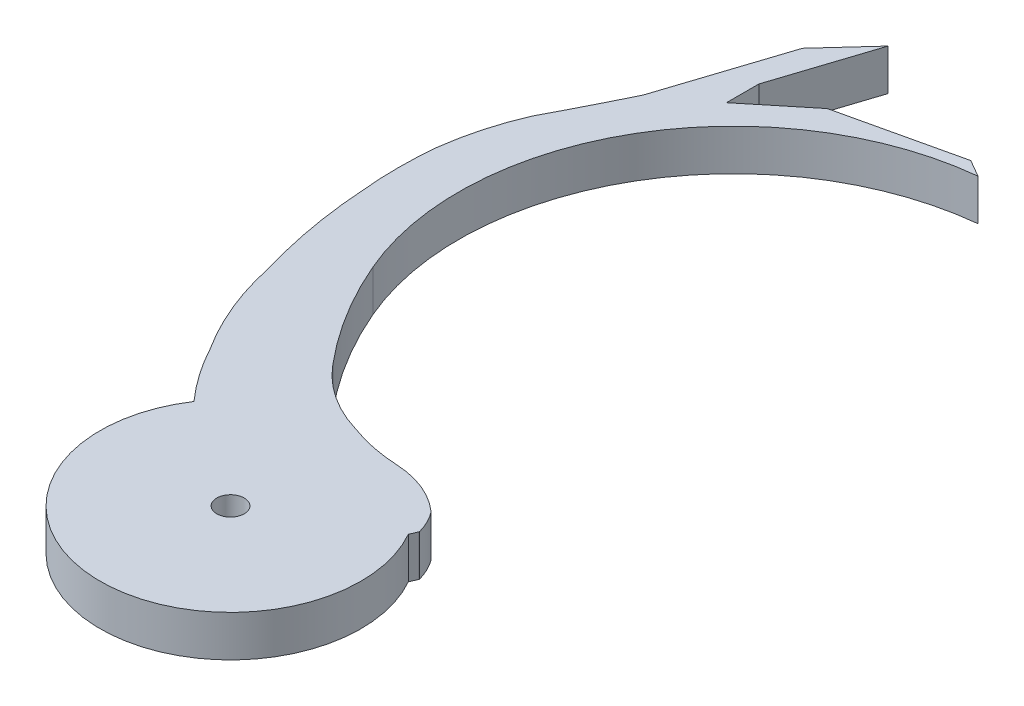
SolidWorks part; units mm, degrees
ref_plane "Front Plane" through (0, 0, 0) normal (0, 0, 1) x (1, 0, 0)
ref_plane "Top Plane" through (0, 0, 0) normal (0, 1, 0) x (1, 0, 0)
ref_plane "Right Plane" through (0, 0, 0) normal (1, 0, 0) x (0, 0, -1)
sketch "Sketch2" plane through (0, 0, 0) normal (0, 1, 0) x (1, 0, 0)
  line L0 (0, 0) -> (-35.9464, 0) construction
  line L1 (-35.9464, 0) -> (41.3976, 0) construction
  line L2 (41.3976, 0) -> (0, 0) construction
  line L3 (0, 0) -> (0, 18.7982) construction
  line L4 (0, 18.7982) -> (0, -23.465) construction
  circle A0 centre (0, 0) radius 20 construction
  circle A1 centre (0, 0) radius 23.465
sketch "Sketch4" plane through (0, 0, 0) normal (0, 1, 0) x (1, 0, 0)
  line L0 (-19.7005, -1.3216) -> (20.2972, -0.8891) construction
  circle A0 centre (0, 0) radius 23.4639 construction
  dimension "D1" = 40
sketch "Sketch5" plane through (0, 0, 0) normal (0, 1, 0) x (1, 0, 0)
  line L0 (-19.9303, -0.0851) -> (20.0695, 0.0365) construction
  dimension "D1" = 40
sketch "Sketch6" plane through (0, 0, 0) normal (0, 1, 0) x (1, 0, 0)
  circle A0 centre (-4.3374, 0.8589) radius 20
sketch "sungu kiri " plane through (0, 0, 0) normal (0, 1, 0) x (1, 0, 0)
  line L0 (-17.9037, 25.6768) -> (-20.2142, 18.582)
  line L1 (-20.2142, 18.582) -> (-20.2142, 16.2232)
  line L2 (-16.1729, 19.5215) -> (-7.6679, 21.4704)
  line L4 (-17.9037, 25.6768) -> (-20.8793, 22.4196)
  line L5 (-20.8793, 22.4196) -> (-23.726, 13.6785)
  line L6 (-23.3814, 7.2187) -> (-21.0655, 13.8643)
  line L8 (-21.0655, 13.8643) -> (-20.2142, 18.582)
  line L9 (-7.6679, 21.4704) -> (-6.4236, 20.7498)
  line L10 (-4.3374, 0.8589) -> (-4.3374, 13.8643) construction
  line L14 (-16.1729, 19.5215) -> (-20.2142, 16.2232)
  line L24 (-4.3374, 0.8589) -> (-4.3374, -17.8442) construction
  arc A0 (-4.3374, -21.9985) -> (-5.1555, -20.3392) centre (-9.0425, -23.287) ccw
  arc A1 (-5.1555, -20.3392) -> (-9.3619, -18.6184) centre (-9.6898, -25.4217) ccw
  arc A2 (-9.3619, -18.6184) -> (-13.1502, -17.8442) centre (-8.7528, -5.9825) cw
  arc A3 (-13.1502, -17.8442) -> (-18.7296, -13.6646) centre (-10.3234, -8.257) cw
  arc A4 (-22.7226, -7.0141) -> (-17.1413, 16.2232) centre (-4.3374, 0.8589) cw
  arc A8 (-23.726, 13.6785) -> (-26.4444, 8.3095) centre (-176.3922, 87.6034) cw
  arc A9 (-26.4444, 8.3095) -> (-27.9369, 2.8451) centre (-7.9567, 0.3238) ccw
  arc A10 (-27.9369, 2.8451) -> (-27.9369, -2.4841) centre (-0.9166, 0.1805) ccw
  arc A11 (-27.9369, -2.4841) -> (-26.4444, -10.8627) centre (10.027, -0.0436) ccw
  arc A12 (-26.4444, -10.8627) -> (-23.4884, -18.0953) centre (-5.339, -6.4571) ccw
  arc A13 (-23.4884, -18.0953) -> (-19.0281, -23.7304) centre (-5.5688, -8.4944) ccw
  arc A14 (-19.0281, -23.7304) -> (-13.725, -28.6503) centre (23.0714, 16.3305) ccw
  arc A18 (-18.7296, -13.6646) -> (-5.4169, -21.3374) centre (-2.7028, -1.2427) ccw construction
  arc A19 (-17.8504, -14.8335) -> (-22.7226, -7.0141) centre (5.1312, 4.9136) cw
  circle A20 centre (-4.3374, 0.8589) radius 20 construction
  circle A21 centre (-12.8438, -27.2612) radius 9.5 construction
  arc A23 (-17.1413, 16.2232) -> (-6.4236, 20.7498) centre (-4.3374, 0.8589) cw
  arc A36 (-4.3446, -22.025) -> (-4.3374, -21.9985) centre (0.3678, -23.287) cw
  circle A37 centre (-12.8438, -27.2612) radius 7.5
  arc A38 (-8.788, -18.6705) -> (-4.5823, -22.5711) centre (-12.8438, -27.2612) ccw construction
  arc A40 (-4.3374, -31.491) -> (-4.3374, -23.0314) centre (4.169, -27.2612) cw construction
  circle A41 centre (-12.8438, -27.2612) radius 1
  arc A42 (-13.725, -17.8021) -> (-4.5823, -22.5711) centre (-12.8438, -27.2612) ccw
  arc A43 (-4.3446, -22.025) -> (-4.5823, -22.5711) centre (-16.7026, -16.9703) cw
  arc A44 (-8.788, -18.6705) -> (-8.8094, -18.6604) centre (-12.8438, -27.2612) ccw
  dimension "D1" = 2
  dimension "D2" = 2
  dimension "D3" = 15
sketch "hjgjg" plane through (0, 0, 0) normal (0, 0, 1) x (1, 0, 0)
  line L0 (0, 0) -> (-35.9464, 0) construction
  line L1 (-35.9464, 0) -> (41.3976, 0) construction
  line L2 (41.3976, 0) -> (0, 0) construction
  line L3 (0, 0) -> (0, 18.7982) construction
  line L4 (0, 18.7982) -> (0, -23.465) construction
  circle A0 centre (0, 0) radius 20 construction
  circle A1 centre (0, 0) radius 23.465
extrude "Boss-Extrude1" add sketch "sungu kiri " along normal blind 3
sketch "Sketch7" plane through (0, 0, 0) normal (0, 1, 0) x (1, 0, 0)
  circle A0 centre (-12.8438, -27.2612) radius 7.5
sketch "Sketch9" plane through (0, 3, 0) normal (0, 1, 0) x (1, 0, 0)
  circle A0 centre (-12.8438, -27.2612) radius 7.5
extrude "Cut-Extrude2" cut sketch "Sketch7" along normal blind 0.5
scale "Scale1" bodies to scale 106 scale about centroid uniform scaling yes scale factor 1.75
